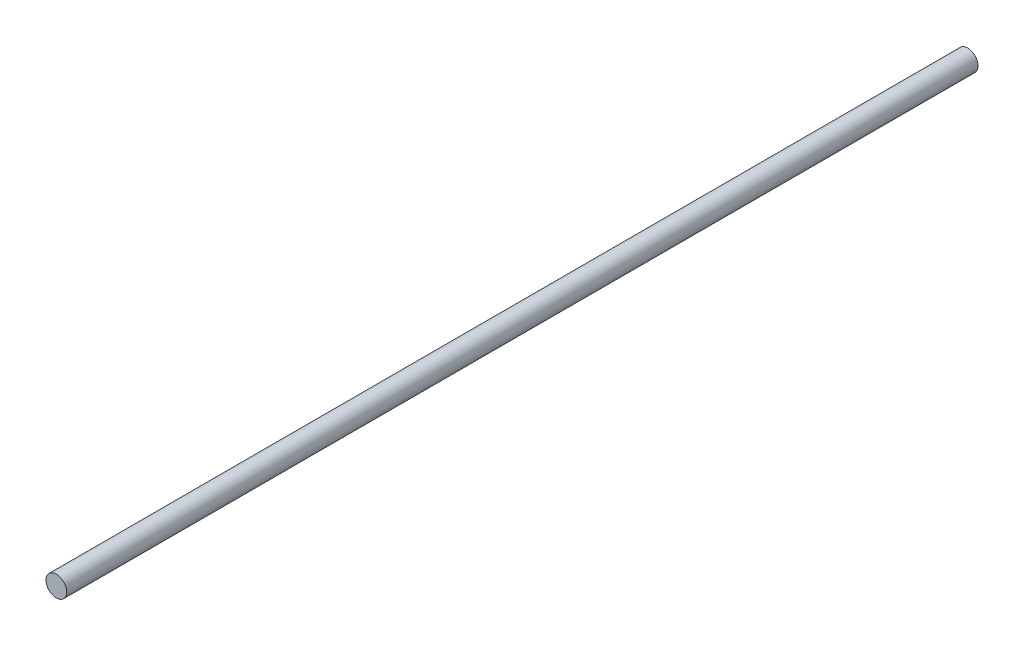
SolidWorks part; units mm, degrees
material "Aluminum"
ref_plane "Front Plane" through (0, 0, 0) normal (0, 0, 1) x (1, 0, 0)
ref_plane "Top Plane" through (0, 0, 0) normal (0, 1, 0) x (1, 0, 0)
ref_plane "Right Plane" through (0, 0, 0) normal (1, 0, 0) x (0, 0, -1)
sketch "Sketch1" plane through (0, 0, 0) normal (0, 0, 1) x (1, 0, 0)
  circle A0 centre (0, 0) radius 3.175
  dimension "D1" = 6.35
extrude "Boss-Extrude1" add sketch "Sketch1" along normal blind 280.035
equation "\"Load\"= 400"
equation "\"Elastic_Modulus\"= 10 * 10 ^ 6"
equation "\"Diameter\"= 0.25"
equation "\"Area\"= 0.049"
equation "\"Length\"= 11.025"
equation "\"Max_Deflection\"= 0.009"
equation "\"D1@Sketch1\"=\"Diameter\""
equation "\"D1@Boss-Extrude1\"=\"Length\""
